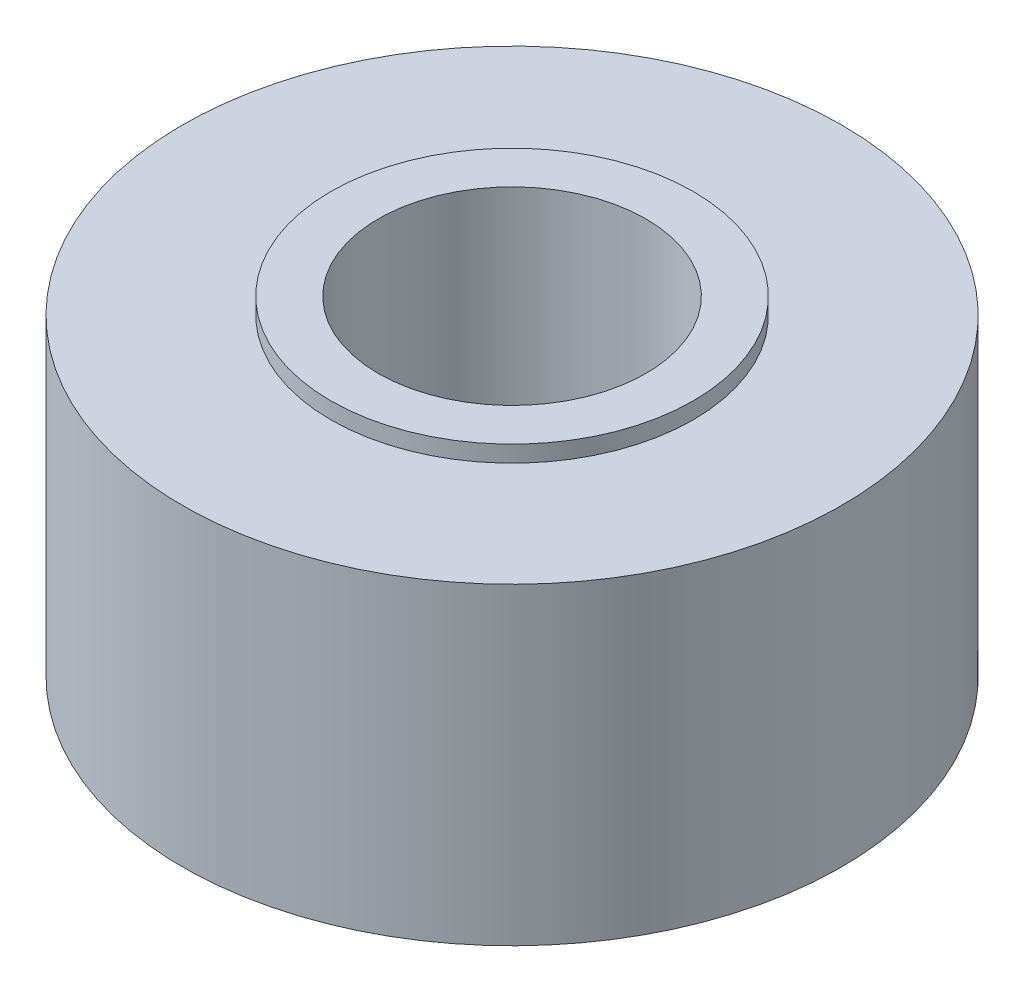
SolidWorks part; units mm, degrees
ref_plane "Alzado" through (0, 0, 0) normal (0, 0, 1) x (1, 0, 0)
ref_plane "Planta" through (0, 0, 0) normal (0, 1, 0) x (1, 0, 0)
ref_plane "Vista lateral" through (0, 0, 0) normal (1, 0, 0) x (0, 0, -1)
sketch "Croquis1" plane through (0, 0, 0) normal (0, 1, 0) x (1, 0, 0)
  circle A0 centre (0, 0) radius 4
  circle A1 centre (0, 0) radius 1.625
  dimension "D1" = 3.25
  dimension "D2" = 8
extrude "Saliente-Extruir1" add sketch "Croquis1" along normal blind 3.8
sketch "Croquis2" plane through (0, 3.8, 0) normal (0, 1, 0) x (1, 0, 0)
  circle A0 centre (0, 0) radius 2.2
  circle A1 centre (0, 0) radius 1.625 construction
  circle A2 centre (0, 0) radius 1.625
  dimension "D1" = 4.4
extrude "Saliente-Extruir2" add sketch "Croquis2" along normal blind 0.2
